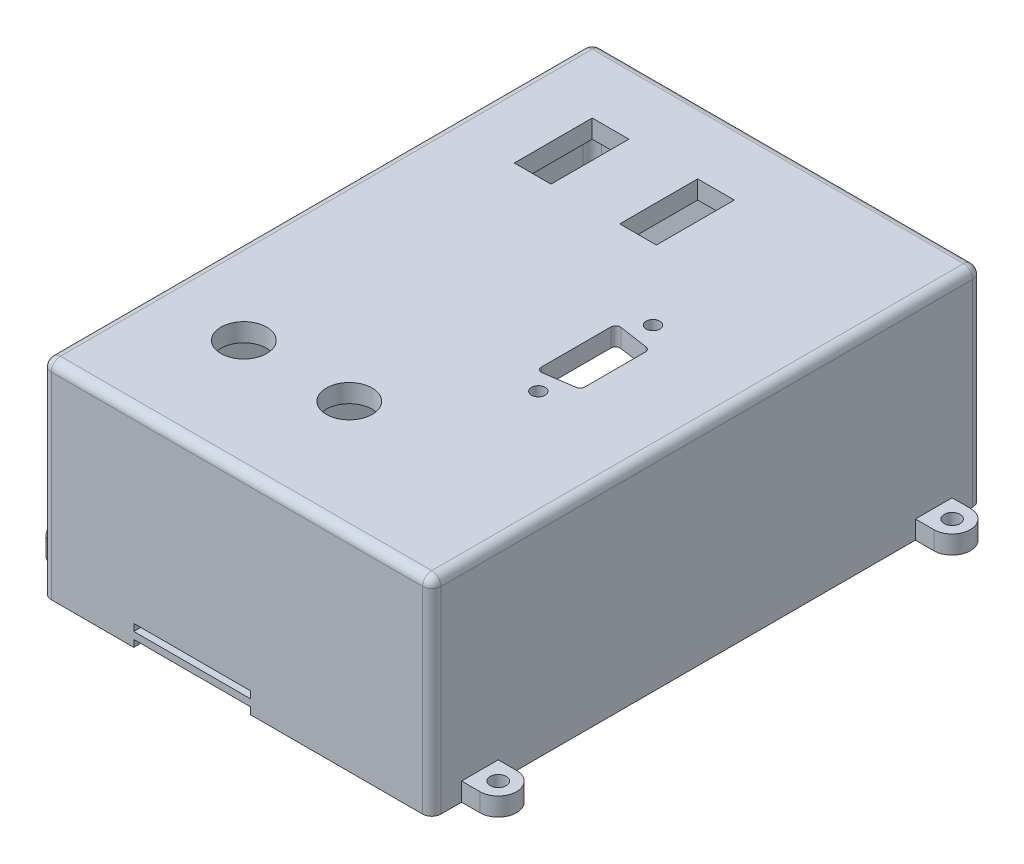
SolidWorks part; units mm, degrees
ref_plane "Front Plane" through (0, 0, 0) normal (0, 0, 1) x (1, 0, 0)
ref_plane "Top Plane" through (0, 0, 0) normal (0, 1, 0) x (1, 0, 0)
ref_plane "Right Plane" through (0, 0, 0) normal (1, 0, 0) x (0, 0, -1)
sketch "Sketch1" plane through (0, 0, 0) normal (0, 1, 0) x (1, 0, 0)
  line L1 (0, 0) -> (85, 0)
  line L2 (0, 0) -> (0, 120)
  line L3 (0, 120) -> (85, 120)
  line L4 (85, 0) -> (85, 120)
  dimension "D1" = 85
  dimension "D2" = 120
extrude "Boss-Extrude1" add sketch "Sketch1" along normal blind 20
ref_plane "Plane1" through (0, 45, 0) normal (0, 1, 0) x (1, 0, 0)
sketch "Sketch2" plane through (0, 45, 0) normal (0, 1, 0) x (1, 0, 0)
  line L0 (0, 120) -> (0, 0) construction
  line L1 (0, 120) -> (85, 120)
  line L2 (0, 120) -> (0, 0)
  line L3 (0, 0) -> (85, 0)
  line L4 (85, 120) -> (85, 0)
  line L5 (85, 120) -> (0, 120) construction
  line L6 (0, 0) -> (85, 0) construction
  line L7 (85, 0) -> (85, 120) construction
  dimension "D1" = 0
  dimension "D2" = 0
  dimension "D3" = 0
loft "Loft1" add profiles "Sketch2" section "Sketch2" section face at (42.5, 20, -60)
shell "Shell2" thickness 4
sketch "Sketch4" plane through (0, 45, 0) normal (0, 1, 0) x (1, 0, 0)
  line L0 (0, 120) -> (0, 0) construction
  line L1 (23, 105) -> (15, 105)
  line L2 (23, 105) -> (23, 88)
  line L3 (23, 88) -> (15, 88)
  line L4 (15, 105) -> (15, 88)
  line L5 (85, 120) -> (0, 120) construction
  line L6 (0, 0) -> (85, 0) construction
  line L7 (38, 88) -> (46, 88)
  line L8 (38, 88) -> (38, 105)
  line L9 (38, 105) -> (46, 105)
  line L10 (46, 88) -> (46, 105)
  circle A0 centre (19, 25) radius 5
  circle A1 centre (42, 25) radius 5
  point P20 (42, 88)
  point P22 (19, 88)
  dimension "D8" = 10
  dimension "D9" = 10
  dimension "D1" = 8
  dimension "D2" = 17
  dimension "D3" = 15
  dimension "D4" = 15
  dimension "D5" = 17
  dimension "D6" = 8
  dimension "D7" = 15
  dimension "D10" = 25
extrude "Cut-Extrude1" cut sketch "Sketch4" against normal blind 20
sketch "Sketch5" plane through (0, 0, 0) normal (0, 0, 1) x (1, 0, 0)
  line L0 (0, 0) -> (85, 0) construction
  line L1 (20, 0) -> (45.5, 0)
  line L2 (20, 0) -> (20, 1.5)
  line L3 (20, 1.5) -> (45.5, 1.5)
  line L4 (45.5, 0) -> (45.5, 1.5)
  line L5 (0, 45) -> (0, 0) construction
  dimension "D1" = 1.5
  dimension "D2" = 25.5
  dimension "D3" = 20
extrude "Cut-Extrude2" cut sketch "Sketch5" against normal blind 20
sketch "Sketch6" plane through (0, 0, 0) normal (0, -1, 0) x (-1, 0, 0)
  line L0 (-85, 0) -> (-85, 120) construction
  line L1 (-85, 6.5) -> (-89, 6.5)
  line L2 (-85, 6.5) -> (-85, 14.5)
  line L3 (-85, 14.5) -> (-89, 14.5)
  line L4 (-89, 6.5) -> (-89, 14.5) construction
  line L5 (0, 120) -> (0, 0) construction
  line L6 (-85, 113.5) -> (-89, 113.5)
  line L7 (-85, 113.5) -> (-85, 105.5)
  line L8 (-85, 105.5) -> (-89, 105.5)
  line L9 (-89, 113.5) -> (-89, 105.5) construction
  line L10 (0, 113.5) -> (4, 113.5)
  line L11 (0, 113.5) -> (0, 105.5)
  line L12 (0, 105.5) -> (4, 105.5)
  line L13 (4, 113.5) -> (4, 105.5) construction
  line L14 (0, 0) -> (-20, 0) construction
  line L15 (0, 14.5) -> (4, 14.5)
  line L16 (0, 14.5) -> (0, 6.5)
  line L17 (0, 6.5) -> (4, 6.5)
  line L18 (4, 14.5) -> (4, 6.5) construction
  line L19 (-85, 120) -> (0, 120) construction
  arc A0 (4, 6.5) -> (4, 14.5) centre (4, 10.5) ccw
  arc A1 (4, 113.5) -> (4, 105.5) centre (4, 109.5) cw
  arc A2 (-89, 113.5) -> (-89, 105.5) centre (-89, 109.5) ccw
  arc A3 (-89, 14.5) -> (-89, 6.5) centre (-89, 10.5) ccw
  circle A4 centre (-89, 10.5) radius 1.75
  circle A5 centre (-89, 109.5) radius 1.75
  circle A6 centre (4, 109.5) radius 1.75
  circle A7 centre (4, 10.5) radius 1.75
  dimension "D4" = 4
  dimension "D5" = 4
  dimension "D6" = 6.5
  dimension "D7" = 3.5
  dimension "D8" = 3.5
  dimension "D9" = 3.5
  dimension "D10" = 3.5
  dimension "D1" = 6.5
  dimension "D2" = 4
  dimension "D3" = 4
extrude "Boss-Extrude2" add sketch "Sketch6" against normal blind 4
sketch "Sketch7" plane through (0, 0, 0) normal (0, 0, 1) x (1, 0, 0)
  line L0 (20, 3.0127) -> (45.5, 3.0127)
  line L1 (45.5, 3.0127) -> (45.5, 4.5256)
  line L2 (45.5, 4.5256) -> (20, 4.5256)
  line L3 (20, 4.5256) -> (20, 3.0127)
extrude "Cut-Extrude3" cut sketch "Sketch7" against normal blind 10 and the other way through all
sketch "Sketch8" plane through (0, 0, 0) normal (0, 1, 0) x (1, 0, 0)
  line L4 (56.5, 68.75) -> (56.5, 51.25)
  line L5 (56.5, 51.25) -> (65, 52.5)
  line L7 (65, 52.5) -> (65, 67.5)
  line L9 (65, 67.5) -> (56.5, 68.75)
  line L10 (85, 0) -> (85, 120) construction
  circle A0 centre (60.75, 72.5) radius 1.5
  circle A1 centre (60.75, 47.5) radius 1.5
  point P4 (54.5634, 48.3428)
  point P8 (56.5, 60)
  point P15 (65, 60)
  point P18 (85, 60)
  dimension "D1" = 3
  dimension "D3" = 25
  dimension "D2" = 12.5
  dimension "D4" = 4.25
  dimension "D6" = 8.5
  dimension "D7" = 15
  dimension "D8" = 17.5
  dimension "D9" = 20
extrude "Cut-Extrude4" cut sketch "Sketch8" against normal blind 10 from surface at 45 starting at face at (42, 45, -96.5)
fillet "Fillet1" radius 1 4 edges at (56.5, 43, -68.75) (65, 43, -67.5) (65, 43, -52.5) (56.5, 43, -51.25)
fillet "Fillet2" radius 2 8 edges at (81, 20.5, -4) (4, 20.5, -4) (4, 20.5, -116) (81, 20.5, -116) (42.5, 41, -4) (42.5, 41, -116) (4, 41, -60) (81, 41, -60)
fillet "Fillet3" radius 2 8 edges
